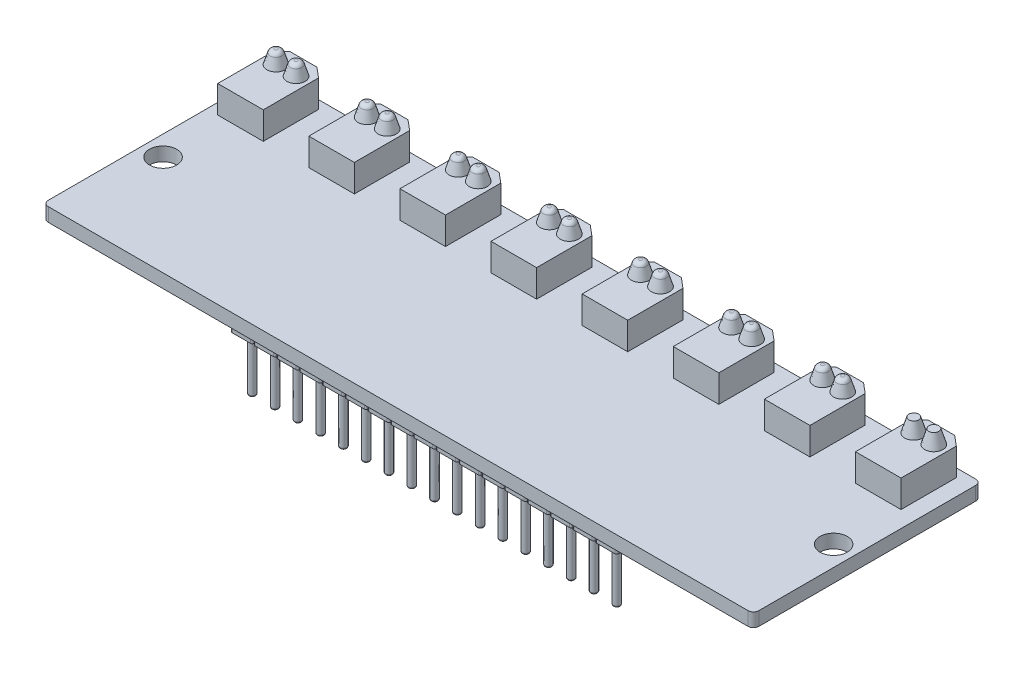
SolidWorks part; units mm, degrees
ref_plane "Front Plane" through (0, 0, 0) normal (0, 0, 1) x (1, 0, 0)
ref_plane "Top Plane" through (0, 0, 0) normal (0, 1, 0) x (1, 0, 0)
ref_plane "Right Plane" through (0, 0, 0) normal (1, 0, 0) x (0, 0, -1)
sketch "Sketch1" plane through (0, 0, 0) normal (0, 1, 0) x (1, 0, 0)
  line L1 (39, -12.5) -> (-39, -12.5)
  line L2 (39, -12.5) -> (39, 12.5)
  line L3 (39, 12.5) -> (-39, 12.5)
  line L4 (-39, -12.5) -> (-39, 12.5)
  line L5 (39, -12.5) -> (-39, 12.5) construction
  line L6 (39, 12.5) -> (-39, -12.5) construction
  point P0 (0, 0)
  dimension "D1" = 25
  dimension "D2" = 78
extrude "Boss-Extrude1" add sketch "Sketch1" along normal blind 1.5
fillet "Fillet1" radius 0.6 4 edges at (39, 0.75, 12.5) (39, 0.75, -12.5) (-39, 0.75, -12.5) (-39, 0.75, 12.5)
sketch "Sketch2" plane through (0, 1.5, 0) normal (0, 1, 0) x (1, 0, 0)
  line L0 (0, 0) -> (0, 12.5) construction
  line L1 (38.4, 12.5) -> (-38.4, 12.5) construction
  line L2 (-39, 11.9) -> (-39, -11.9) construction
  circle A0 centre (-36.8, -1.5) radius 1.5
  circle A1 centre (36.8, -1.5) radius 1.5
  dimension "D1" = 3
  dimension "D2" = 14
  dimension "D3" = 2.2
extrude "Cut-Extrude1" cut sketch "Sketch2" against normal blind 1.5
sketch "Sketch3" plane through (0, 1.5, 0) normal (0, 1, 0) x (1, 0, 0)
  line L0 (38.4, 12.5) -> (-38.4, 12.5) construction
  line L1 (-36.8668, 12.5) -> (-33.914, 12.5)
  line L2 (-37.8, 11.5668) -> (-37.8, 5.5)
  line L3 (-37.8, 5.5) -> (-32.8, 5.5)
  line L4 (-32.8, 11.5668) -> (-32.8, 5.5)
  line L5 (-37.4112, 11.9556) -> (-32.8, 5.5) construction
  line L6 (-37.8, 5.5) -> (-33.217, 11.9161) construction
  line L7 (-39, 11.9) -> (-39, -11.9) construction
  line L8 (-36.8668, 12.5) -> (-37.8, 11.5668)
  line L9 (-33.914, 12.5) -> (-32.8, 11.5668)
  line L10 (-22.8, 11.5668) -> (-22.8, 5.5)
  line L11 (-23.914, 12.5) -> (-22.8, 11.5668)
  line L12 (-26.8668, 12.5) -> (-23.914, 12.5)
  line L13 (-26.8668, 12.5) -> (-27.8, 11.5668)
  line L14 (-27.8, 11.5668) -> (-27.8, 5.5)
  line L15 (-27.8, 5.5) -> (-22.8, 5.5)
  line L16 (-12.8, 11.5668) -> (-12.8, 5.5)
  line L17 (-13.914, 12.5) -> (-12.8, 11.5668)
  line L18 (-16.8668, 12.5) -> (-13.914, 12.5)
  line L19 (-16.8668, 12.5) -> (-17.8, 11.5668)
  line L20 (-17.8, 11.5668) -> (-17.8, 5.5)
  line L21 (-17.8, 5.5) -> (-12.8, 5.5)
  line L22 (-2.8, 11.5668) -> (-2.8, 5.5)
  line L23 (-3.914, 12.5) -> (-2.8, 11.5668)
  line L24 (-6.8668, 12.5) -> (-3.914, 12.5)
  line L25 (-6.8668, 12.5) -> (-7.8, 11.5668)
  line L26 (-7.8, 11.5668) -> (-7.8, 5.5)
  line L27 (-7.8, 5.5) -> (-2.8, 5.5)
  line L28 (7.2, 11.5668) -> (7.2, 5.5)
  line L29 (6.086, 12.5) -> (7.2, 11.5668)
  line L30 (3.1332, 12.5) -> (6.086, 12.5)
  line L31 (3.1332, 12.5) -> (2.2, 11.5668)
  line L32 (2.2, 11.5668) -> (2.2, 5.5)
  line L33 (2.2, 5.5) -> (7.2, 5.5)
  line L34 (17.2, 11.5668) -> (17.2, 5.5)
  line L35 (16.086, 12.5) -> (17.2, 11.5668)
  line L36 (13.1332, 12.5) -> (16.086, 12.5)
  line L37 (13.1332, 12.5) -> (12.2, 11.5668)
  line L38 (12.2, 11.5668) -> (12.2, 5.5)
  line L39 (12.2, 5.5) -> (17.2, 5.5)
  line L40 (27.2, 11.5668) -> (27.2, 5.5)
  line L41 (26.086, 12.5) -> (27.2, 11.5668)
  line L42 (23.1332, 12.5) -> (26.086, 12.5)
  line L43 (23.1332, 12.5) -> (22.2, 11.5668)
  line L44 (22.2, 11.5668) -> (22.2, 5.5)
  line L45 (22.2, 5.5) -> (27.2, 5.5)
  line L46 (37.2, 11.5668) -> (37.2, 5.5)
  line L47 (36.086, 12.5) -> (37.2, 11.5668)
  line L48 (33.1332, 12.5) -> (36.086, 12.5)
  line L49 (33.1332, 12.5) -> (32.2, 11.5668)
  line L50 (32.2, 11.5668) -> (32.2, 5.5)
  line L51 (32.2, 5.5) -> (37.2, 5.5)
  point P0 (-35.3, 9)
  dimension "D1" = 5
  dimension "D2" = 7
  dimension "D3" = 0
  dimension "D4" = 1.2
  dimension "D5" = 8
extrude "Boss-Extrude2" add sketch "Sketch3" along normal blind 3
sketch "Sketch4" plane through (0, 4.5, 0) normal (0, 1, 0) x (1, 0, 0)
  line L0 (-37.8, 11.5668) -> (-37.8, 5.5) construction
  line L1 (-32.8, 5.5) -> (-32.8, 11.5668) construction
  line L2 (-37.8, 5.5) -> (-32.8, 5.5) construction
  line L3 (-37.8, 5.5) -> (-32.8, 5.5) construction
  circle A0 centre (-36.4, 10.4996) radius 1
  circle A1 centre (-34.2, 10.4996) radius 1
  circle A2 centre (-26.4, 10.4996) radius 1 construction
  circle A3 centre (-24.2, 10.4996) radius 1 construction
  circle A4 centre (-16.4, 10.4996) radius 1 construction
  circle A5 centre (-14.2, 10.4996) radius 1 construction
  circle A6 centre (-6.4, 10.4996) radius 1 construction
  circle A7 centre (-4.2, 10.4996) radius 1 construction
  circle A8 centre (3.6, 10.4996) radius 1 construction
  circle A9 centre (5.8, 10.4996) radius 1 construction
  circle A10 centre (13.6, 10.4996) radius 1 construction
  circle A11 centre (15.8, 10.4996) radius 1 construction
  circle A12 centre (23.6, 10.4996) radius 1 construction
  circle A13 centre (25.8, 10.4996) radius 1 construction
  circle A14 centre (33.6, 10.4996) radius 1 construction
  circle A15 centre (35.8, 10.4996) radius 1 construction
  circle A16 centre (-26.4, 10.4996) radius 1
  circle A17 centre (-24.2, 10.4996) radius 1
  circle A18 centre (-16.4, 10.4996) radius 1
  circle A19 centre (-14.2, 10.4996) radius 1
  circle A20 centre (-6.4, 10.4996) radius 1
  circle A21 centre (-4.2, 10.4996) radius 1
  circle A22 centre (3.6, 10.4996) radius 1
  circle A23 centre (5.8, 10.4996) radius 1
  circle A24 centre (13.6, 10.4996) radius 1
  circle A25 centre (15.8, 10.4996) radius 1
  circle A26 centre (23.6, 10.4996) radius 1
  circle A27 centre (25.8, 10.4996) radius 1
  circle A28 centre (33.6, 10.4996) radius 1
  circle A29 centre (35.8, 10.4996) radius 1
  dimension "D1" = 2
  dimension "D2" = 2
  dimension "D5" = 4.9996
  dimension "D6" = 4.9996
  dimension "D3" = 1.4
  dimension "D4" = 1.4
  dimension "D7" = 8
  dimension "D8" = 8
extrude "Boss-Extrude7" add sketch "Sketch4" along normal blind 1.5 draft 17
fillet "Fillet4" radius 0.5 14 edges at (-36.4, 6, -9.9582) (-34.2, 6, -9.9582) (-26.4, 6, -9.9582) (-24.2, 6, -9.9582) (-16.4, 6, -9.9582) (-14.2, 6, -9.9582) (-6.4, 6, -9.9582) (-4.2, 6, -9.9582) (25.8, 6, -9.9582) (23.6, 6, -9.9582) (15.8, 6, -9.9582) (13.6, 6, -9.9582) (5.8, 6, -9.9582) (3.6, 6, -9.9582)
sketch "Sketch5" plane through (0, 0, 0) normal (0, -1, 0) x (1, 0, 0)
  line L0 (38.4, -12.5) -> (-38.4, -12.5) construction
  line L1 (-22.5, 10.9) -> (-20.1, 10.9)
  line L2 (-22.5, 10.9) -> (-22.5, 8.5)
  line L3 (-22.5, 8.5) -> (-20.1, 8.5)
  line L4 (-20.1, 10.9) -> (-20.1, 8.5)
  line L5 (-22.5, 10.9) -> (-20.1, 8.5) construction
  line L6 (-22.5, 8.5) -> (-20.1, 10.9) construction
  line L7 (-20, 10.9) -> (-20, 8.5)
  line L8 (-17.6, 10.9) -> (-17.6, 8.5)
  line L9 (-20, 8.5) -> (-17.6, 8.5)
  line L10 (-17.5, 10.9) -> (-17.5, 8.5)
  line L11 (-15.1, 10.9) -> (-15.1, 8.5)
  line L12 (-17.5, 8.5) -> (-15.1, 8.5)
  line L13 (-15, 10.9) -> (-15, 8.5)
  line L14 (-12.6, 10.9) -> (-12.6, 8.5)
  line L15 (-15, 8.5) -> (-12.6, 8.5)
  line L16 (-12.5, 10.9) -> (-12.5, 8.5)
  line L17 (-10.1, 10.9) -> (-10.1, 8.5)
  line L18 (-12.5, 8.5) -> (-10.1, 8.5)
  line L19 (-10, 10.9) -> (-10, 8.5)
  line L20 (-7.6, 10.9) -> (-7.6, 8.5)
  line L21 (-10, 8.5) -> (-7.6, 8.5)
  line L22 (-7.5, 10.9) -> (-7.5, 8.5)
  line L23 (-5.1, 10.9) -> (-5.1, 8.5)
  line L24 (-7.5, 8.5) -> (-5.1, 8.5)
  line L25 (-5, 10.9) -> (-5, 8.5)
  line L26 (-2.6, 10.9) -> (-2.6, 8.5)
  line L27 (-5, 8.5) -> (-2.6, 8.5)
  line L28 (-2.5, 10.9) -> (-2.5, 8.5)
  line L29 (-0.1, 10.9) -> (-0.1, 8.5)
  line L30 (-2.5, 8.5) -> (-0.1, 8.5)
  line L31 (0, 10.9) -> (0, 8.5)
  line L32 (2.4, 10.9) -> (2.4, 8.5)
  line L33 (0, 8.5) -> (2.4, 8.5)
  line L34 (2.5, 10.9) -> (2.5, 8.5)
  line L35 (4.9, 10.9) -> (4.9, 8.5)
  line L36 (2.5, 8.5) -> (4.9, 8.5)
  line L37 (5, 10.9) -> (5, 8.5)
  line L38 (7.4, 10.9) -> (7.4, 8.5)
  line L39 (5, 8.5) -> (7.4, 8.5)
  line L40 (7.5, 10.9) -> (7.5, 8.5)
  line L41 (9.9, 10.9) -> (9.9, 8.5)
  line L42 (7.5, 8.5) -> (9.9, 8.5)
  line L43 (10, 10.9) -> (10, 8.5)
  line L44 (12.4, 10.9) -> (12.4, 8.5)
  line L45 (10, 8.5) -> (12.4, 8.5)
  line L46 (12.5, 10.9) -> (12.5, 8.5)
  line L47 (14.9, 10.9) -> (14.9, 8.5)
  line L48 (12.5, 8.5) -> (14.9, 8.5)
  line L49 (15, 10.9) -> (15, 8.5)
  line L50 (17.4, 10.9) -> (17.4, 8.5)
  line L51 (15, 8.5) -> (17.4, 8.5)
  line L52 (17.5, 10.9) -> (17.5, 8.5)
  line L53 (19.9, 10.9) -> (19.9, 8.5)
  line L54 (17.5, 8.5) -> (19.9, 8.5)
  line L55 (20, 10.9) -> (20, 8.5)
  line L56 (22.4, 10.9) -> (22.4, 8.5)
  line L57 (20, 8.5) -> (22.4, 8.5)
  line L58 (-20, 10.9) -> (-20, 8.5)
  line L59 (-17.6, 10.9) -> (-17.6, 8.5)
  line L60 (-20, 8.5) -> (-17.6, 8.5)
  line L61 (-20, 10.9) -> (-17.6, 10.9)
  line L62 (-17.5, 10.9) -> (-17.5, 8.5)
  line L63 (-15.1, 10.9) -> (-15.1, 8.5)
  line L64 (-17.5, 8.5) -> (-15.1, 8.5)
  line L65 (-17.5, 10.9) -> (-15.1, 10.9)
  line L66 (-15, 10.9) -> (-15, 8.5)
  line L67 (-12.6, 10.9) -> (-12.6, 8.5)
  line L68 (-15, 8.5) -> (-12.6, 8.5)
  line L69 (-15, 10.9) -> (-12.6, 10.9)
  line L70 (-12.5, 10.9) -> (-12.5, 8.5)
  line L71 (-10.1, 10.9) -> (-10.1, 8.5)
  line L72 (-12.5, 8.5) -> (-10.1, 8.5)
  line L73 (-12.5, 10.9) -> (-10.1, 10.9)
  line L74 (-10, 10.9) -> (-10, 8.5)
  line L75 (-7.6, 10.9) -> (-7.6, 8.5)
  line L76 (-10, 8.5) -> (-7.6, 8.5)
  line L77 (-10, 10.9) -> (-7.6, 10.9)
  line L78 (-7.5, 10.9) -> (-7.5, 8.5)
  line L79 (-5.1, 10.9) -> (-5.1, 8.5)
  line L80 (-7.5, 8.5) -> (-5.1, 8.5)
  line L81 (-7.5, 10.9) -> (-5.1, 10.9)
  line L82 (-5, 10.9) -> (-5, 8.5)
  line L83 (-2.6, 10.9) -> (-2.6, 8.5)
  line L84 (-5, 8.5) -> (-2.6, 8.5)
  line L85 (-5, 10.9) -> (-2.6, 10.9)
  line L86 (-2.5, 10.9) -> (-2.5, 8.5)
  line L87 (-0.1, 10.9) -> (-0.1, 8.5)
  line L88 (-2.5, 8.5) -> (-0.1, 8.5)
  line L89 (-2.5, 10.9) -> (-0.1, 10.9)
  line L90 (0, 10.9) -> (0, 8.5)
  line L91 (2.4, 10.9) -> (2.4, 8.5)
  line L92 (0, 8.5) -> (2.4, 8.5)
  line L93 (0, 10.9) -> (2.4, 10.9)
  line L94 (2.5, 10.9) -> (2.5, 8.5)
  line L95 (4.9, 10.9) -> (4.9, 8.5)
  line L96 (2.5, 8.5) -> (4.9, 8.5)
  line L97 (2.5, 10.9) -> (4.9, 10.9)
  line L98 (5, 10.9) -> (5, 8.5)
  line L99 (7.4, 10.9) -> (7.4, 8.5)
  line L100 (5, 8.5) -> (7.4, 8.5)
  line L101 (5, 10.9) -> (7.4, 10.9)
  line L102 (7.5, 10.9) -> (7.5, 8.5)
  line L103 (9.9, 10.9) -> (9.9, 8.5)
  line L104 (7.5, 8.5) -> (9.9, 8.5)
  line L105 (7.5, 10.9) -> (9.9, 10.9)
  line L106 (10, 10.9) -> (10, 8.5)
  line L107 (12.4, 10.9) -> (12.4, 8.5)
  line L108 (10, 8.5) -> (12.4, 8.5)
  line L109 (10, 10.9) -> (12.4, 10.9)
  line L110 (12.5, 10.9) -> (12.5, 8.5)
  line L111 (14.9, 10.9) -> (14.9, 8.5)
  line L112 (12.5, 8.5) -> (14.9, 8.5)
  line L113 (12.5, 10.9) -> (14.9, 10.9)
  line L114 (15, 10.9) -> (15, 8.5)
  line L115 (17.4, 10.9) -> (17.4, 8.5)
  line L116 (15, 8.5) -> (17.4, 8.5)
  line L117 (15, 10.9) -> (17.4, 10.9)
  line L118 (17.5, 10.9) -> (17.5, 8.5)
  line L119 (19.9, 10.9) -> (19.9, 8.5)
  line L120 (17.5, 8.5) -> (19.9, 8.5)
  line L121 (17.5, 10.9) -> (19.9, 10.9)
  line L122 (20, 10.9) -> (20, 8.5)
  line L123 (22.4, 10.9) -> (22.4, 8.5)
  line L124 (20, 8.5) -> (22.4, 8.5)
  line L125 (20, 10.9) -> (22.4, 10.9)
  line L126 (-39, -11.9) -> (-39, 11.9) construction
  point P0 (-21.3, 9.7)
  dimension "D1" = 2.4
  dimension "D2" = 2.4
  dimension "D3" = 21
  dimension "D6" = 16.5
  dimension "D4" = 18
  dimension "D5" = 18
extrude "Boss-Extrude12" add sketch "Sketch5" along normal blind 2 contours L65 L10 L12 L11 | L69 L13 L15 L14 | L73 L16 L18 L17 | L77 L19 L21 L20 | L81 L22 L24 L23 | L61 L7 L9 L8 | L85 L25 L27 L26 | L89 L28 L30 L29 | L93 L31 L33 L32 | L97 L34 L36 L35 | L101 L37 L39 L38 | L105 L40 L42 L41 | L109 L43 L45 L44 | L113 L46 L48 L47 | L117 L49 L51 L50 | L121 L52 L54 L53 | L125 L55 L57 L56
sketch "Sketch6" plane through (0, -2, 0) normal (0, -1, 0) x (1, 0, 0)
  line L0 (-20, 8.5) -> (-17.6, 8.5) construction
  line L1 (-20, 10.9) -> (-17.6, 10.9) construction
  circle A0 centre (-18.8, 9.7) radius 0.375
  circle A1 centre (-16.3, 9.7) radius 0.375
  circle A2 centre (-13.8, 9.7) radius 0.375
  circle A3 centre (-11.3, 9.7) radius 0.375
  circle A4 centre (-8.8, 9.7) radius 0.375
  circle A5 centre (-6.3, 9.7) radius 0.375
  circle A6 centre (-3.8, 9.7) radius 0.375
  circle A7 centre (-1.3, 9.7) radius 0.375
  circle A8 centre (1.2, 9.7) radius 0.375
  circle A9 centre (3.7, 9.7) radius 0.375
  circle A10 centre (6.2, 9.7) radius 0.375
  circle A11 centre (8.7, 9.7) radius 0.375
  circle A12 centre (11.2, 9.7) radius 0.375
  circle A13 centre (13.7, 9.7) radius 0.375
  circle A14 centre (16.2, 9.7) radius 0.375
  circle A15 centre (18.7, 9.7) radius 0.375
  circle A16 centre (21.2, 9.7) radius 0.375
  point P4 (-18.8, 10.9)
  dimension "D1" = 1.2
  dimension "D2" = 1.2
  dimension "D3" = 0.75
  dimension "D4" = 17
extrude "Boss-Extrude13" add sketch "Sketch6" along normal blind 6
fillet "Fillet5" radius 0.2 4 edges at (-17.6, -1, 10.9) (-17.6, -1, 8.5) (-20, -1, 8.5) (-20, -1, 10.9)
fillet "Fillet7" radius 0.2 64 edges at (22.4, -1, 8.5) (20, -1, 8.5) (19.9, -1, 8.5) (17.5, -1, 8.5) (17.4, -1, 8.5) (15, -1, 8.5) (14.9, -1, 8.5) (12.5, -1, 8.5) (12.4, -1, 8.5) (10, -1, 8.5) (9.9, -1, 8.5) (7.5, -1, 8.5) (7.4, -1, 8.5) (5, -1, 8.5) (4.9, -1, 8.5) (2.5, -1, 8.5) (2.4, -1, 8.5) (0, -1, 8.5) (-0.1, -1, 8.5) (-2.5, -1, 8.5) (-2.6, -1, 8.5) (-5, -1, 8.5) (-5.1, -1, 8.5) (-7.5, -1, 8.5) (-7.6, -1, 8.5) (-10, -1, 8.5) (-10.1, -1, 8.5) (-12.5, -1, 8.5) (-12.6, -1, 8.5) (-15, -1, 8.5) (-15.1, -1, 8.5) (-17.5, -1, 8.5) (22.4, -1, 10.9) (20, -1, 10.9) (19.9, -1, 10.9) (17.5, -1, 10.9) (17.4, -1, 10.9) (15, -1, 10.9) (14.9, -1, 10.9) (12.5, -1, 10.9) (12.4, -1, 10.9) (10, -1, 10.9) (9.9, -1, 10.9) (7.5, -1, 10.9) (7.4, -1, 10.9) (5, -1, 10.9) (4.9, -1, 10.9) (2.5, -1, 10.9) (2.4, -1, 10.9) (0, -1, 10.9) (-0.1, -1, 10.9) (-2.5, -1, 10.9) (-2.6, -1, 10.9) (-5, -1, 10.9) (-5.1, -1, 10.9) (-7.5, -1, 10.9) (-7.6, -1, 10.9) (-10, -1, 10.9) (-10.1, -1, 10.9) (-12.5, -1, 10.9) (-12.6, -1, 10.9) (-15, -1, 10.9) (-15.1, -1, 10.9) (-17.5, -1, 10.9)
fillet "Fillet8" radius 0.2 17 edges at (21.2, -8, 9.325) (18.7, -8, 9.325) (16.2, -8, 9.325) (13.7, -8, 9.325) (11.2, -8, 9.325) (8.7, -8, 9.325) (6.2, -8, 9.325) (3.7, -8, 9.325) (1.2, -8, 9.325) (-1.3, -8, 9.325) (-3.8, -8, 9.325) (-6.3, -8, 9.325) (-8.8, -8, 9.325) (-11.3, -8, 9.325) (-13.8, -8, 9.325) (-16.3, -8, 9.325) (-18.8, -8, 9.325)
